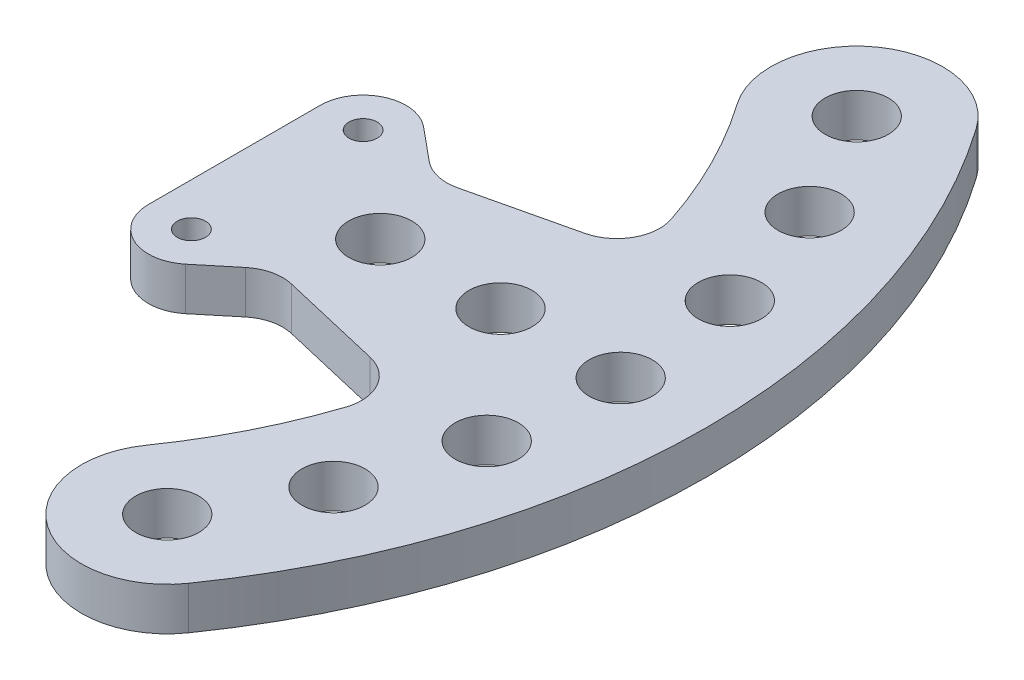
SolidWorks part; units mm, degrees
ref_plane "Front Plane" through (0, 0, 0) normal (0, 0, 1) x (1, 0, 0)
ref_plane "Top Plane" through (0, 0, 0) normal (0, 1, 0) x (1, 0, 0)
ref_plane "Right Plane" through (0, 0, 0) normal (1, 0, 0) x (0, 0, -1)
sketch "Sketch1" plane through (0, 0, 0) normal (0, 1, 0) x (1, 0, 0)
  line L0 (0, 0) -> (88.9, 0) construction
  line L1 (67.7251, 15.875) -> (52.4846, 12.3026)
  line L2 (46.99, 13.5905) -> (42.1455, 17.5946)
  line L3 (31.75, 12.7) -> (31.75, -12.7)
  line L4 (46.99, -13.5905) -> (42.1455, -17.5946)
  line L5 (67.7251, -15.875) -> (52.4846, -12.3026)
  line L6 (38.1, 12.7) -> (38.1, -12.7) construction
  line L7 (72.8226, 50.9909) -> (0, 0) construction
  circle A0 centre (0, 0) radius 88.9 construction
  arc A1 (72.8226, 50.9909) -> (72.8226, -50.9909) centre (0, 0) cw construction
  arc A2 (83.2258, -58.2754) -> (83.2258, 58.2754) centre (0, 0) ccw
  arc A3 (72.301, 24.0626) -> (62.4194, 43.7065) centre (0, 0) ccw
  arc A4 (62.4194, -43.7065) -> (83.2258, -58.2754) centre (72.8226, -50.9909) ccw
  arc A5 (83.2258, 58.2754) -> (62.4194, 43.7065) centre (72.8226, 50.9909) ccw
  arc A6 (46.99, 13.5905) -> (52.4846, 12.3026) centre (51.0355, 18.485) ccw
  arc A7 (72.301, 24.0626) -> (67.7251, 15.875) centre (66.2759, 22.0574) cw
  arc A8 (42.1455, 17.5946) -> (31.75, 12.7) centre (38.1, 12.7) ccw
  arc A9 (42.1455, -17.5946) -> (31.75, -12.7) centre (38.1, -12.7) cw
  arc A10 (72.301, -24.0626) -> (67.7251, -15.875) centre (66.2759, -22.0574) ccw
  arc A11 (46.99, -13.5905) -> (52.4846, -12.3026) centre (51.0355, -18.485) cw
  arc A12 (72.301, -24.0626) -> (62.4194, -43.7065) centre (0, 0) cw
  circle A13 centre (38.1, 12.7) radius 2.0828
  circle A14 centre (88.9, 0) radius 4.6736
  circle A15 centre (87.0634, -17.9771) radius 4.6736
  circle A16 centre (81.6294, -35.2115) radius 4.6736
  circle A17 centre (72.8226, -50.9909) radius 4.6736
  circle A18 centre (87.0634, 17.9771) radius 4.6736
  circle A19 centre (81.6294, 35.2115) radius 4.6736
  circle A20 centre (72.8226, 50.9909) radius 4.6736
  circle A21 centre (71.12, 0) radius 4.6736
  circle A22 centre (53.34, 0) radius 4.6736
  circle A23 centre (38.1, -12.7) radius 2.0828
  point P4 (88.9, 0)
  point P31 (31.75, 0)
  point P43 (0, 0)
  point P49 (0, 0)
  dimension "D2" = 35
  dimension "D1" = 177.8
  dimension "D3" = 25.4
  dimension "D4" = 6.35
  dimension "D7" = 4.1656
  dimension "D10" = 9.3472
  dimension "D5" = 38.1
  dimension "D6" = 31.75
  dimension "D8" = 25.4
  dimension "D9" = 15.24
  dimension "D13" = 3
  dimension "D11" = 4
  dimension "D12" = 4
extrude "Boss-Extrude1" add sketch "Sketch1" along normal blind 6.35
sketch "Sketch2" plane through (0, 6.35, 0) normal (0, 1, 0) x (1, 0, 0)
  circle A0 centre (88.9, 0) radius 4.6736 construction
  circle A1 centre (88.9, 0) radius 4.6736
extrude "Boss-Extrude2" [suppressed] add sketch "Sketch2" against normal up to surface (6.35 mm away)
